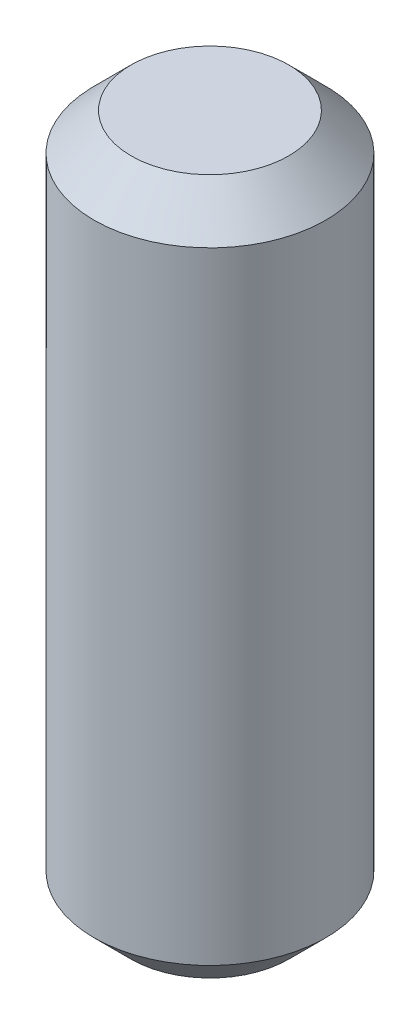
SolidWorks part; units mm, degrees
ref_plane "Front Plane" through (0, 0, 0) normal (0, 0, 1) x (1, 0, 0)
ref_plane "Top Plane" through (0, 0, 0) normal (0, 1, 0) x (1, 0, 0)
ref_plane "Right Plane" through (0, 0, 0) normal (1, 0, 0) x (0, 0, -1)
sketch "Sketch1" plane through (0, 0, 0) normal (0, 1, 0) x (1, 0, 0)
  circle A0 centre (0, 0) radius 2.5
  dimension "D1" = 5
extrude "Boss-Extrude1" add sketch "Sketch1" along normal blind 15
chamfer "Chamfer1" distance 0.8 2 edges at (0, 0, 2.5) (0, 15, 2.5)
